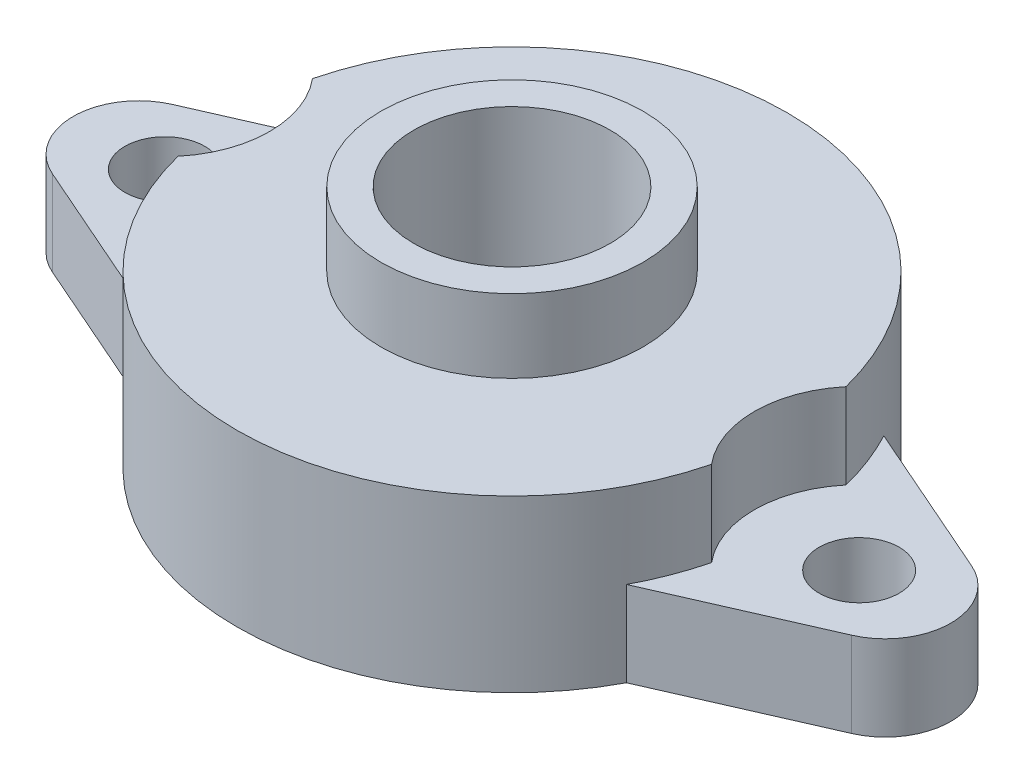
SolidWorks part; units mm, degrees
ref_plane "Front Plane" through (0, 0, 0) normal (0, 0, 1) x (1, 0, 0)
ref_plane "Top Plane" through (0, 0, 0) normal (0, 1, 0) x (1, 0, 0)
ref_plane "Right Plane" through (0, 0, 0) normal (1, 0, 0) x (0, 0, -1)
sketch "Sketch3" plane through (0, 0, 0) normal (0, 1, 0) x (1, 0, 0)
  line L0 (33.5, 0) -> (-33.5, 0) construction
  line L1 (26.5, 0) -> (-26.5, 0) construction
  line L2 (-33.5, 0) -> (-40.9427, 0) construction
  line L3 (0, 17.9669) -> (0, -17.9669) construction
  line L4 (-30.5092, 4.5785) -> (0, 17.9669)
  line L5 (-30.5092, -4.5785) -> (0, -17.9669)
  line L6 (30.5092, -4.5785) -> (0, -17.9669)
  line L7 (30.5092, 4.5785) -> (0, 17.9669)
  circle A0 centre (-26.5, 0) radius 3.05
  circle A1 centre (26.5, 0) radius 3.05
  circle A2 centre (0, 0) radius 21
  arc A3 (-30.5092, -4.5785) -> (-30.5092, 4.5785) centre (-28.5, 0) cw
  arc A4 (30.5092, -4.5785) -> (30.5092, 4.5785) centre (28.5, 0) ccw
  point P3 (-33.5, 0)
  point P4 (0, 0)
  point P8 (0, 0)
  point P12 (0, 16.5461)
  point P16 (0, 0)
  point P17 (-39.1443, 0)
  point P21 (-37.927, 0)
  point P22 (0, 18.62)
  point P23 (-33.5, 0)
  point P24 (0, 16.9841)
  point P25 (0, 18.8137)
  point P26 (0, 16.6626)
  point P30 (0, 17.9669)
  point P31 (0, 0)
  point P32 (0, 0)
  dimension "D3" = 6.1
  dimension "D4" = 42
  dimension "D5" = 5
  dimension "D1" = 67
  dimension "D2" = 53
extrude "Boss-Extrude1" add sketch "Sketch3" along normal blind 6.5 contours L5 A2 L6 | L6 A2 L7 L4 L5 | L7 A2 L4 | L6 A4 L7 A2 A1 | A3 L5 A2 L4 A0
sketch "Sketch4" plane through (0, 6.5, 0) normal (0, 1, 0) x (1, 0, 0)
  arc A0 (20.3632, 5.1322) -> (-20.3632, 5.1322) centre (0, 0) ccw
  arc A1 (-20.3632, -5.1322) -> (-20.3632, 5.1322) centre (-26.5, 0) ccw
  arc A2 (20.3632, 5.1322) -> (20.3632, -5.1322) centre (26.5, 0) ccw
  arc A3 (-20.3632, 5.1322) -> (-20.3632, -5.1322) centre (-26.5, 0) ccw construction
  arc A4 (20.3632, -5.1322) -> (20.3632, 5.1322) centre (26.5, 0) ccw construction
  arc A5 (20.3632, -5.1322) -> (20.3632, 5.1322) centre (0, 0) ccw construction
  arc A6 (-20.3632, 5.1322) -> (-20.3632, -5.1322) centre (0, 0) ccw construction
  arc A7 (-20.3632, -5.1322) -> (20.3632, -5.1322) centre (0, 0) ccw
  dimension "D1" = 16
extrude "Boss-Extrude2" add sketch "Sketch4" along normal blind 6.5
sketch "Sketch5" plane through (0, 13, 0) normal (0, 1, 0) x (1, 0, 0)
  circle A0 centre (0, 0) radius 10
  dimension "D1" = 20
extrude "Boss-Extrude3" add sketch "Sketch5" along normal blind 5.6
sketch "Sketch6" plane through (0, 18.6, 0) normal (0, 1, 0) x (1, 0, 0)
  circle A0 centre (0, 0) radius 7.5
  dimension "D1" = 15
extrude "Cut-Extrude1" cut sketch "Sketch6" against normal through all
